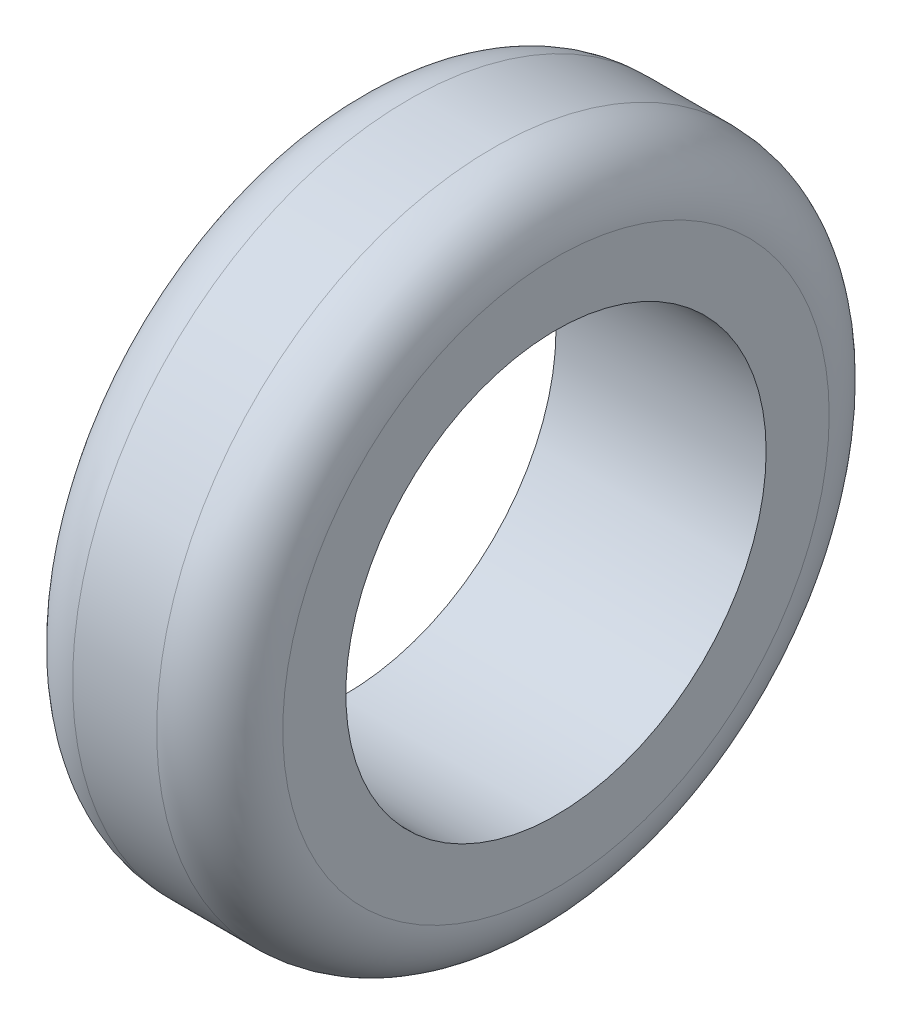
SolidWorks part; units mm, degrees
material "BUTYL"
ref_plane "Plano frontal" through (0, 0, 0) normal (0, 0, 1) x (1, 0, 0)
ref_plane "Plano superior" through (0, 0, 0) normal (0, 1, 0) x (1, 0, 0)
ref_plane "Plano direito" through (0, 0, 0) normal (1, 0, 0) x (0, 0, -1)
sketch "Esboço1" plane through (0, 0, 0) normal (1, 0, 0) x (0, 0, -1)
  circle A0 centre (0, 0) radius 80
  circle A1 centre (0, 0) radius 50
  circle A4 centre (0, 0) radius 50 construction
  dimension "D1" = 30
extrude "Ressalto-extrusão1" add sketch "Esboço1" along normal up to surface (50 mm away)
fillet "Filete1" radius 15 2 edges at (50, 0, -80) (0, 0, -80)
shell "Casca1" thickness 3
